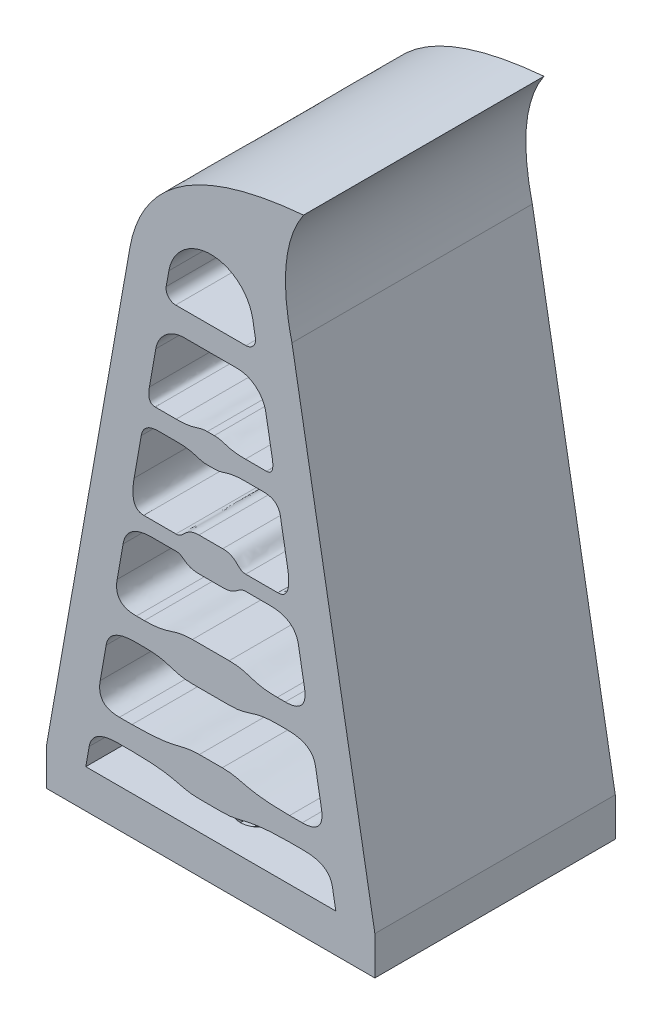
SolidWorks part; units mm, degrees
ref_plane "Front Plane" through (0, 0, 0) normal (0, 0, 1) x (1, 0, 0)
ref_plane "Top Plane" through (0, 0, 0) normal (0, 1, 0) x (1, 0, 0)
ref_plane "Right Plane" through (0, 0, 0) normal (1, 0, 0) x (0, 0, -1)
sketch "Sketch2" plane through (0, 0, 0) normal (0, 0, 1) x (1, 0, 0)
  line L4 (1.2363, 30.75) -> (-1.2363, 30.75)
  line L6 (8.5918, 29) -> (-8.5918, 29) construction
  line L15 (-4.3633, 52.981) -> (-4.8449, 50.25)
  line L17 (-3.623, 29.65) -> (-6.9747, 29.65)
  line L40 (-3.623, 28.1) -> (-6.1208, 28.1)
  line L61 (1.2363, 27.25) -> (-1.2363, 27.25)
  line L62 (-1.2363, 27.25) -> (-2.7363, 27.25) construction
  line L63 (10.3551, 19) -> (-10.3551, 19) construction
  line L64 (-2.7363, 27.25) -> (-2.7363, 28.1) construction
  line L65 (-6.1208, 28.1) -> (-8.7505, 28.1) construction
  line L66 (-8.7505, 28.1) -> (-9.1208, 26) construction
  line L67 (-2.7363, 28.1) -> (-3.623, 28.1) construction
  line L68 (-6.9747, 29.65) -> (-8.4772, 29.65) construction
  line L69 (-8.4772, 29.65) -> (-7.9747, 32.5) construction
  line L70 (-1.2363, 30.75) -> (-2.7363, 30.75) construction
  line L71 (-2.7363, 30.75) -> (-2.7363, 29.65) construction
  line L72 (-2.7363, 29.65) -> (-3.623, 29.65) construction
  line L73 (0.3668, 40.5) -> (-0.3668, 40.5)
  line L74 (25.87, 39) -> (-25.87, 39) construction
  line L75 (-3.6023, 40) -> (-5.7877, 40)
  line L76 (-3.6023, 38) -> (-5.4341, 38)
  line L77 (0.3668, 37.5) -> (-0.3668, 37.5)
  line L78 (-0.3668, 37.5) -> (-1.4668, 37.5) construction
  line L79 (-1.4668, 37.5) -> (-1.4668, 38) construction
  line L80 (-5.4341, 38) -> (-7.0049, 38) construction
  line L81 (-7.0049, 38) -> (-7.2341, 36.7) construction
  line L82 (-1.4668, 38) -> (-3.6023, 38) construction
  line L83 (-5.7877, 40) -> (-6.6522, 40) construction
  line L84 (-6.6522, 40) -> (-6.3877, 41.5) construction
  line L85 (-0.3668, 40.5) -> (-1.4668, 40.5) construction
  line L86 (-1.4668, 40.5) -> (-1.4668, 40) construction
  line L87 (-1.4668, 40) -> (-3.6023, 40) construction
  line L88 (-0.3668, 40.5) -> (-0.3668, 39) construction
  line L89 (-0.3668, 39) -> (-0.3668, 37.5) construction
  line L90 (-3.6023, 40) -> (-3.6023, 39) construction
  line L91 (-3.6023, 39) -> (-3.6023, 38) construction
  line L92 (5.0653, 49) -> (-5.0653, 49) construction
  line L93 (4.8449, 50.25) -> (-4.8449, 50.25)
  line L94 (5.2857, 47.75) -> (-5.2857, 47.75)
  line L95 (-5.2857, 47.75) -> (-6.3877, 41.5)
  line L96 (12.6473, 6) -> (13, 4)
  line L104 (-7.2341, 36.7) -> (-7.9747, 32.5)
  line L120 (-9.1208, 26) -> (-9.738, 22.5)
  line L121 (-10.8841, 16) -> (-11.5012, 12.5)
  line L122 (0, 0) -> (0, 86.9787) construction
  line L123 (13, 4) -> (-13, 4)
  line L124 (17.0617, 4) -> (8.4407, 52.8922)
  line L125 (-12.6473, 6) -> (-13, 4)
  line L126 (1.193, 11) -> (3.393, 11) construction
  line L127 (3.393, 11) -> (3.393, 10.2) construction
  line L128 (3.393, 10.2) -> (8.193, 10.2) construction
  line L129 (9.5012, 10.2) -> (11.9068, 10.2) construction
  line L130 (11.9068, 10.2) -> (11.5012, 12.5) construction
  line L131 (9.6473, 7.8) -> (12.33, 7.8) construction
  line L132 (12.33, 7.8) -> (12.6473, 6) construction
  line L133 (1.193, 7) -> (3.393, 7) construction
  line L134 (3.393, 7) -> (3.393, 7.8) construction
  line L135 (3.393, 7.8) -> (8.193, 7.8) construction
  line L136 (8.193, 10.2) -> (9.5012, 10.2)
  line L137 (8.193, 7.8) -> (9.6473, 7.8)
  line L138 (10.8841, 16) -> (11.5012, 12.5)
  line L139 (3.6023, 39) -> (3.6023, 38) construction
  line L140 (3.6023, 40) -> (3.6023, 39) construction
  line L141 (1.9104, 21) -> (4.1104, 21) construction
  line L142 (4.1104, 21) -> (4.1104, 20.2) construction
  line L143 (4.1104, 20.2) -> (6.9104, 20.2) construction
  line L144 (7.738, 20.2) -> (10.1435, 20.2) construction
  line L145 (10.1435, 20.2) -> (9.738, 22.5) construction
  line L146 (7.8841, 17.8) -> (10.5667, 17.8) construction
  line L147 (10.5667, 17.8) -> (10.8841, 16) construction
  line L148 (1.9104, 17) -> (4.1104, 17) construction
  line L149 (4.1104, 17) -> (4.1104, 17.8) construction
  line L150 (4.1104, 17.8) -> (6.9104, 17.8) construction
  line L151 (0.3668, 37.5) -> (1.4668, 37.5) construction
  line L152 (1.4668, 37.5) -> (1.4668, 38) construction
  line L153 (1.4668, 38) -> (3.6023, 38) construction
  line L154 (0.3668, 40.5) -> (1.4668, 40.5) construction
  line L155 (1.4668, 40.5) -> (1.4668, 40) construction
  line L156 (1.4668, 40) -> (3.6023, 40) construction
  line L157 (5.4341, 38) -> (7.0049, 38) construction
  line L158 (7.0049, 38) -> (7.2341, 36.7) construction
  line L159 (5.7877, 40) -> (6.6522, 40) construction
  line L160 (6.6522, 40) -> (6.3877, 41.5) construction
  line L161 (1.2363, 27.25) -> (2.7363, 27.25) construction
  line L162 (2.7363, 27.25) -> (2.7363, 28.1) construction
  line L163 (-8.4257, 52.9771) -> (-17.0617, 4)
  line L164 (1.9104, 17) -> (-1.9104, 17)
  line L165 (-6.9104, 17.8) -> (-7.8841, 17.8)
  line L166 (-6.9104, 20.2) -> (-7.738, 20.2)
  line L167 (1.9104, 21) -> (-1.9104, 21)
  line L168 (-1.9104, 17) -> (-4.1104, 17) construction
  line L169 (-4.1104, 17) -> (-4.1104, 17.8) construction
  line L170 (-7.8841, 17.8) -> (-10.5667, 17.8) construction
  line L171 (-10.5667, 17.8) -> (-10.8841, 16) construction
  line L172 (-4.1104, 17.8) -> (-6.9104, 17.8) construction
  line L173 (-7.738, 20.2) -> (-10.1435, 20.2) construction
  line L174 (-10.1435, 20.2) -> (-9.738, 22.5) construction
  line L175 (-1.9104, 21) -> (-4.1104, 21) construction
  line L176 (-4.1104, 21) -> (-4.1104, 20.2) construction
  line L177 (-4.1104, 20.2) -> (-6.9104, 20.2) construction
  line L178 (2.7363, 28.1) -> (3.623, 28.1) construction
  line L179 (1.2363, 30.75) -> (2.7363, 30.75) construction
  line L180 (2.7363, 30.75) -> (2.7363, 29.65) construction
  line L181 (2.7363, 29.65) -> (3.623, 29.65) construction
  line L182 (6.1208, 28.1) -> (8.7505, 28.1) construction
  line L183 (8.7505, 28.1) -> (9.1208, 26) construction
  line L184 (6.9747, 29.65) -> (8.4772, 29.65) construction
  line L185 (12.1184, 9) -> (-12.1184, 9) construction
  line L186 (1.193, 7) -> (-1.193, 7)
  line L187 (-1.193, 7) -> (-3.393, 7) construction
  line L188 (-3.393, 7) -> (-3.393, 7.8) construction
  line L189 (-8.193, 7.8) -> (-9.6473, 7.8)
  line L190 (-9.6473, 7.8) -> (-12.33, 7.8) construction
  line L191 (-12.33, 7.8) -> (-12.6473, 6) construction
  line L192 (-3.393, 7.8) -> (-8.193, 7.8) construction
  line L193 (-9.5012, 10.2) -> (-11.9068, 10.2) construction
  line L194 (-11.9068, 10.2) -> (-11.5012, 12.5) construction
  line L195 (-8.193, 10.2) -> (-9.5012, 10.2)
  line L196 (-1.193, 11) -> (-3.393, 11) construction
  line L197 (-3.393, 11) -> (-3.393, 10.2) construction
  line L198 (-3.393, 10.2) -> (-8.193, 10.2) construction
  line L199 (1.193, 11) -> (-1.193, 11)
  line L200 (8.4772, 29.65) -> (7.9747, 32.5) construction
  line L201 (6.9104, 20.2) -> (7.738, 20.2)
  line L202 (6.9104, 17.8) -> (7.8841, 17.8)
  line L203 (9.1208, 26) -> (9.738, 22.5)
  line L204 (7.2341, 36.7) -> (7.9747, 32.5)
  line L205 (0.3668, 39) -> (0.3668, 37.5) construction
  line L206 (0.3668, 40.5) -> (0.3668, 39) construction
  line L207 (3.6023, 38) -> (5.4341, 38)
  line L208 (3.6023, 40) -> (5.7877, 40)
  line L209 (3.623, 28.1) -> (6.1208, 28.1)
  line L210 (3.623, 29.65) -> (6.9747, 29.65)
  line L211 (5.2857, 47.75) -> (6.3877, 41.5)
  line L212 (4.3633, 52.981) -> (4.8449, 50.25)
  line L216 (-8.4257, 52.9771) -> (-6.5572, 63.5742) construction
  line L217 (-6.5572, 63.5742) -> (9.6435, 65) construction
  line L219 (9.6435, 65) -> (6.628, 60.4981) construction
  line L220 (6.628, 60.4981) -> (8.4407, 52.8922) construction
  line L221 (17.0617, 0) -> (-17.0617, 0)
  line L223 (17.0617, 4) -> (17.0617, 0)
  line L224 (-17.0617, 4) -> (-17.0617, 0)
  line L226 (0, 62.854) -> (0, 84.5784) construction
  arc A1 (4.3633, 52.981) -> (-4.3633, 52.981) centre (0, 52.2116) ccw
  spline S0 degree 2 poles (-6.9747, 29.65) (-8.4772, 29.65) (-7.9747, 32.5) knots 0 0 0 1 1 1
  spline S1 degree 2 poles (-6.1208, 28.1) (-8.7505, 28.1) (-9.1208, 26) knots 0 0 0 1 1 1
  spline S2 degree 3 poles (-1.2363, 30.75) (-2.7363, 30.75) (-2.7363, 29.65) (-3.623, 29.65) knots 0 0 0 0 1 1 1 1
  spline S3 degree 3 poles (-1.2363, 27.25) (-2.7363, 27.25) (-2.7363, 28.1) (-3.623, 28.1) knots 0 0 0 0 1 1 1 1
  spline S4 degree 2 poles (-5.7877, 40) (-6.6522, 40) (-6.3877, 41.5) knots 0 0 0 1 1 1
  spline S5 degree 2 poles (-5.4341, 38) (-7.0049, 38) (-7.2341, 36.7) knots 0 0 0 1 1 1
  spline S6 degree 3 poles (-0.3668, 40.5) (-1.4668, 40.5) (-1.4668, 40) (-3.6023, 40) knots 0 0 0 0 1 1 1 1
  spline S7 degree 3 poles (-0.3668, 37.5) (-1.4668, 37.5) (-1.4668, 38) (-3.6023, 38) knots 0 0 0 0 1 1 1 1
  spline S8 degree 3 poles (1.193, 11) (3.393, 11) (3.393, 10.2) (8.193, 10.2) knots 0 0 0 0 1 1 1 1
  spline S9 degree 2 poles (9.5012, 10.2) (11.9068, 10.2) (11.5012, 12.5) knots 0 0 0 1 1 1
  spline S10 degree 2 poles (9.6473, 7.8) (12.33, 7.8) (12.6473, 6) knots 0 0 0 1 1 1
  spline S11 degree 3 poles (1.193, 7) (3.393, 7) (3.393, 7.8) (8.193, 7.8) knots 0 0 0 0 1 1 1 1
  spline S12 degree 3 poles (1.9104, 21) (4.1104, 21) (4.1104, 20.2) (6.9104, 20.2) knots 0 0 0 0 1 1 1 1
  spline S13 degree 2 poles (7.738, 20.2) (10.1435, 20.2) (9.738, 22.5) knots 0 0 0 1 1 1
  spline S14 degree 3 poles (-1.9104, 17) (-4.1104, 17) (-4.1104, 17.8) (-6.9104, 17.8) knots 0 0 0 0 1 1 1 1
  spline S15 degree 2 poles (-7.8841, 17.8) (-10.5667, 17.8) (-10.8841, 16) knots 0 0 0 1 1 1
  spline S16 degree 2 poles (-7.738, 20.2) (-10.1435, 20.2) (-9.738, 22.5) knots 0 0 0 1 1 1
  spline S17 degree 3 poles (-1.9104, 21) (-4.1104, 21) (-4.1104, 20.2) (-6.9104, 20.2) knots 0 0 0 0 1 1 1 1
  spline S18 degree 3 poles (-1.193, 7) (-3.393, 7) (-3.393, 7.8) (-8.193, 7.8) knots 0 0 0 0 1 1 1 1
  spline S19 degree 2 poles (-9.6473, 7.8) (-12.33, 7.8) (-12.6473, 6) knots 0 0 0 1 1 1
  spline S20 degree 2 poles (-9.5012, 10.2) (-11.9068, 10.2) (-11.5012, 12.5) knots 0 0 0 1 1 1
  spline S21 degree 3 poles (-1.193, 11) (-3.393, 11) (-3.393, 10.2) (-8.193, 10.2) knots 0 0 0 0 1 1 1 1
  spline S22 degree 2 poles (7.8841, 17.8) (10.5667, 17.8) (10.8841, 16) knots 0 0 0 1 1 1
  spline S23 degree 3 poles (1.9104, 17) (4.1104, 17) (4.1104, 17.8) (6.9104, 17.8) knots 0 0 0 0 1 1 1 1
  spline S24 degree 3 poles (0.3668, 37.5) (1.4668, 37.5) (1.4668, 38) (3.6023, 38) knots 0 0 0 0 1 1 1 1
  spline S25 degree 3 poles (0.3668, 40.5) (1.4668, 40.5) (1.4668, 40) (3.6023, 40) knots 0 0 0 0 1 1 1 1
  spline S26 degree 2 poles (5.4341, 38) (7.0049, 38) (7.2341, 36.7) knots 0 0 0 1 1 1
  spline S27 degree 2 poles (5.7877, 40) (6.6522, 40) (6.3877, 41.5) knots 0 0 0 1 1 1
  spline S28 degree 3 poles (1.2363, 27.25) (2.7363, 27.25) (2.7363, 28.1) (3.623, 28.1) knots 0 0 0 0 1 1 1 1
  spline S29 degree 3 poles (1.2363, 30.75) (2.7363, 30.75) (2.7363, 29.65) (3.623, 29.65) knots 0 0 0 0 1 1 1 1
  spline S30 degree 2 poles (6.1208, 28.1) (8.7505, 28.1) (9.1208, 26) knots 0 0 0 1 1 1
  spline S31 degree 2 poles (6.9747, 29.65) (8.4772, 29.65) (7.9747, 32.5) knots 0 0 0 1 1 1
  spline S32 degree 2 poles (-8.4257, 52.9771) (-6.5572, 63.5742) (9.6435, 65) knots 0 0 0 1 1 1
  spline S33 degree 2 poles (9.6435, 65) (6.628, 60.4981) (8.4407, 52.8922) knots 0 0 0 1 1 1
  point P6 (0, 30.75)
  point P28 (0, 40.5)
  point P47 (0, 27.25)
  point P55 (9.4294, 24.25)
  point P61 (7.4747, 72.2344)
  point P64 (0, 77.7267)
  point P72 (0, 49)
  point P76 (0, 9)
  point P91 (0, 11)
  point P92 (0, 7)
  point P98 (0, 39)
  point P99 (0, 19)
  point P100 (0, 29)
  point P139 (0, 21)
  point P140 (0, 17)
  point P141 (0, 37.5)
  point P142 (0, 47.75)
  point P143 (0, 50.25)
  point P145 (7.9772, 52.8067)
  point P148 (8.6208, 65)
  point P149 (7.4747, 65)
  point P150 (0, 0)
  point P152 (7.8852, 65)
  point P154 (-7.4747, 52.8067)
  point P155 (-5.378, 67.4258)
  point P156 (3.393, 56.5356)
  point P159 (-3.393, 56.5089)
  point P160 (3.393, 54.5208)
  point P161 (-3.393, 55.0887)
  point P162 (0, 0)
  point P163 (-3.8784, 52.889)
  point P164 (7.4747, 65)
  point P165 (-6.0731, 63.4837)
  point P166 (6.628, 60.4981)
  point P167 (11.0012, 65)
  point P168 (9.238, 65)
  point P169 (0, 0)
  point P170 (0, 84.5784)
  point P171 (0, 86.9787)
  point P172 (-0.3668, 37.5)
  point P173 (5.1764, 29.65)
  point P174 (4.283, 28.1)
  point P175 (-3.4764, 28.1)
  point P176 (-0.8961, 27.25)
  point P177 (-4.0223, 28.1)
  point P181 (-1.2363, 27.25)
  point P183 (3.623, 29.65)
  point P187 (-0.3668, 40.5)
  point P189 (0, 0)
  point P190 (1.9104, 21)
  dimension "D4" = 10
  dimension "D22" = 1.2
  dimension "D23" = 5
  dimension "D29" = 2.2
  dimension "D34" = 2
  dimension "D26" = 5
  dimension "D8" = 1
  dimension "D20" = 65
  dimension "D6" = 0.9
  dimension "D7" = 3.5
  dimension "D9" = 26
  dimension "D10" = 3
  dimension "D11" = 3.5
  dimension "D12" = 2.3867
  dimension "D13" = 1.75
  dimension "D14" = 1.5
  dimension "D15" = 3
  dimension "D16" = 0.65
  dimension "D17" = 1
  dimension "D18" = 10
  dimension "D21" = 2
  dimension "D24" = 2.2
  dimension "D25" = 2
  dimension "D27" = 1.2
  dimension "D28" = 7
  dimension "D30" = 3
  dimension "D31" = 3.5
  dimension "D32" = 10
  dimension "D33" = 3
  dimension "D35" = 3
  dimension "D36" = 2
  dimension "D37" = 3.5
  dimension "D38" = 3
  dimension "D39" = 3
  dimension "D40" = 0.6
  dimension "D41" = 1.8
  dimension "D42" = 1.5
  dimension "D43" = 1.3
  dimension "D45" = 1.1
  dimension "D46" = 10
  dimension "D47" = 2.5
  dimension "D48" = 1.25
  dimension "D49" = 4
  dimension "D50" = 1
  dimension "D51" = 10
  dimension "D52" = 4
  dimension "D53" = 4
extrude "Boss-Extrude1" add sketch "Sketch2" along normal blind 25
fillet "Fillet1" radius 1 2 edges at (-4.8449, 50.25, 12.5) (4.8449, 50.25, 12.5)
fillet "Fillet2" radius 3 2 edges at (-5.2857, 47.75, 12.5) (5.2857, 47.75, 12.5)
sketch "Sketch7" plane through (0, 0, 0) normal (0, -1, 0) x (1, 0, 0)
  line L0 (0.0617, 0) -> (0.0617, 25) construction
  line L2 (17.0617, 12.5) -> (-17.0617, 12.5) construction
  line L3 (17.0617, 25) -> (17.0617, 0) construction
  line L4 (-17.0617, 25) -> (-17.0617, 0) construction
  circle A2 centre (-7.4383, 12.5) radius 1
  circle A4 centre (0.0617, 20) radius 1
  circle A6 centre (7.5617, 12.5) radius 1
  circle A8 centre (0.0617, 5) radius 1
  point P19 (0, 0)
  point P20 (0, 0)
  point P21 (0, 0)
  point P22 (0, 0)
  point P23 (0, 0)
  dimension "D5" = 2
  dimension "D6" = 17
  dimension "D1" = 7.5
  dimension "D2" = 7.5
  dimension "D3" = 15
  dimension "D4" = 15
extrude "Cut-Extrude2" cut sketch "Sketch7" against normal up to next
sketch "Sketch9" plane through (0, 4, 0) normal (0, 1, 0) x (1, 0, 0)
  circle A0 centre (0.0617, -5) radius 2
  circle A1 centre (0.0617, -5) radius 1
  circle A2 centre (0.0617, -5) radius 1
  circle A3 centre (7.5617, -12.5) radius 1
  circle A4 centre (7.5617, -12.5) radius 1
  circle A5 centre (0.0617, -20) radius 1
  circle A6 centre (0.0617, -20) radius 1
  circle A7 centre (-7.4383, -12.5) radius 1
  circle A8 centre (-7.4383, -12.5) radius 1
  circle A9 centre (7.5617, -12.5) radius 2
  circle A10 centre (0.0617, -20) radius 2
  circle A11 centre (-7.4383, -12.5) radius 2
  dimension "D1" = 0
  dimension "D2" = 0
  dimension "D3" = 0
  dimension "D4" = 0
  dimension "D5" = 1
extrude "Cut-Extrude3" cut sketch "Sketch9" against normal blind 2
